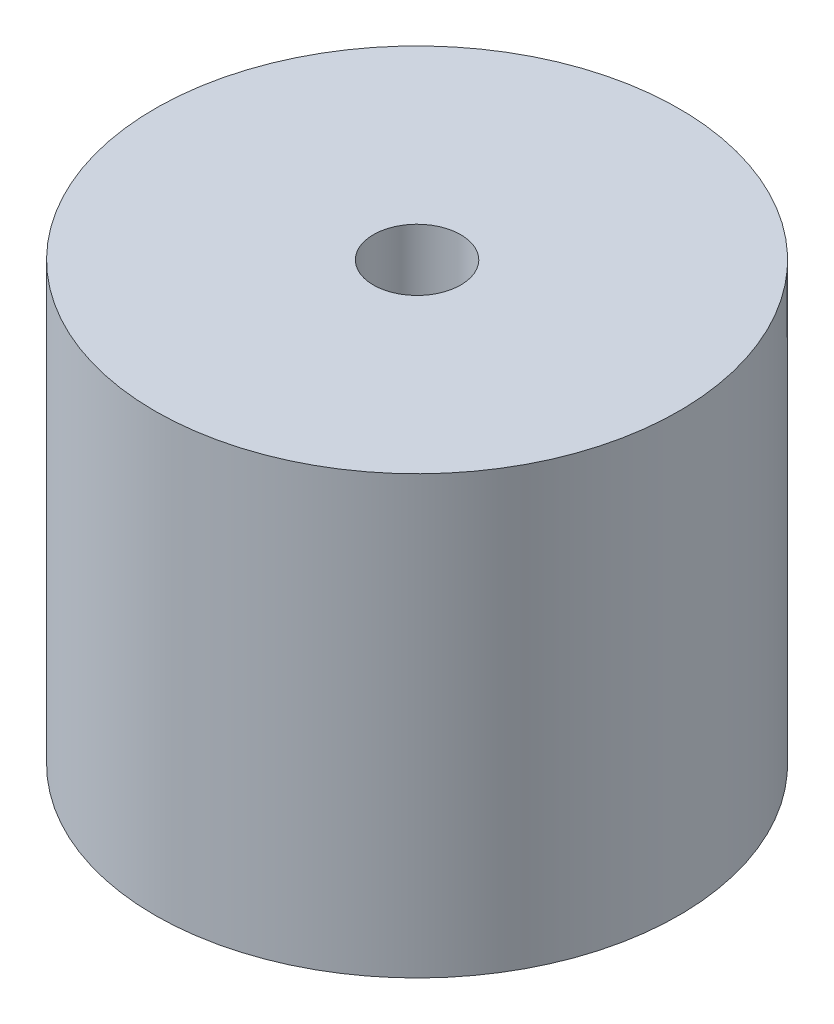
SolidWorks part; units mm, degrees
ref_plane "Front Plane" through (0, 0, 0) normal (0, 0, 1) x (1, 0, 0)
ref_plane "Top Plane" through (0, 0, 0) normal (0, 1, 0) x (1, 0, 0)
ref_plane "Right Plane" through (0, 0, 0) normal (1, 0, 0) x (0, 0, -1)
sketch "Sketch1" plane through (0, 0, 0) normal (0, 1, 0) x (1, 0, 0)
  circle A0 centre (0, 0) radius 18
  dimension "D1" = 36
extrude "Boss-Extrude1" add sketch "Sketch1" along normal blind 30
sketch "Sketch2" plane through (0, 30, 0) normal (0, 1, 0) x (1, 0, 0)
  circle A0 centre (0, 0) radius 18 construction
  circle A1 centre (0, 0) radius 18
  circle A2 centre (0, 0) radius 3
  dimension "D1" = 6
extrude "Cut-Extrude1" cut sketch "Sketch2" against normal through all contours A2
